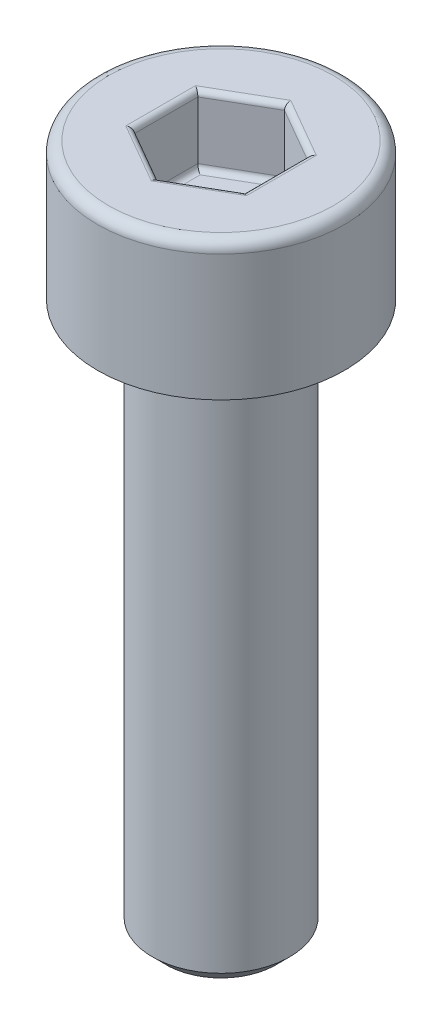
SolidWorks part; units mm, degrees
ref_plane "Front Plane" through (0, 0, 0) normal (0, 0, 1) x (1, 0, 0)
ref_plane "Top Plane" through (0, 0, 0) normal (0, 1, 0) x (1, 0, 0)
ref_plane "Right Plane" through (0, 0, 0) normal (1, 0, 0) x (0, 0, -1)
sketch "Sketch1" plane through (0, 0, 0) normal (0, 0, 1) x (1, 0, 0)
  line L0 (0, 0) -> (0, -47.0967) construction
  line L1 (0, -12.5) -> (-1.25, -12.5)
  line L2 (-1.25, -12.5) -> (-1.25, -2.5)
  line L3 (-1.25, -2.5) -> (-2.25, -2.5)
  line L4 (-2.25, -2.5) -> (-2.25, 0)
  line L5 (-2.25, 0) -> (0, 0)
  line L6 (0, 0) -> (0, -12.5)
  dimension "D1" = 10
  dimension "d" = 2.5
  dimension "k" = 2.5
  dimension "dk" = 4.5
revolve "Revolve1" add sketch "Sketch1" angle 360 about L0
chamfer "Chamfer1" distance 0.25 angle 45 2 edges at (0, -2.5, 1.25) (0, -12.5, 1.25)
fillet "Fillet1" radius 0.2 1 edges at (0, 0, 2.25)
sketch "Sketch2" plane through (0, 0, 0) normal (0, 1, 0) x (1, 0, 0)
  line L1 (0, 1.1547) -> (-1, 0.5774)
  line L2 (-1, 0.5774) -> (-1, -0.5774)
  line L3 (-1, -0.5774) -> (0, -1.1547)
  line L4 (0, -1.1547) -> (1, -0.5774)
  line L5 (1, -0.5774) -> (1, 0.5774)
  line L6 (1, 0.5774) -> (0, 1.1547)
  circle A0 centre (0, 0) radius 1 construction
  dimension "s" = 2
extrude "Cut-Extrude1" cut sketch "Sketch2" against normal blind 1.25
fillet "Fillet2" radius 0.1 12 edges at (-0.5, 0, -0.866) (-1, 0, 0) (-0.5, 0, 0.866) (0.5, 0, 0.866) (1, 0, 0) (0.5, 0, -0.866) (1, -1.25, 0) (0.5, -1.25, 0.866) (-0.5, -1.25, 0.866) (-1, -1.25, 0) (-0.5, -1.25, -0.866) (0.5, -1.25, -0.866)
